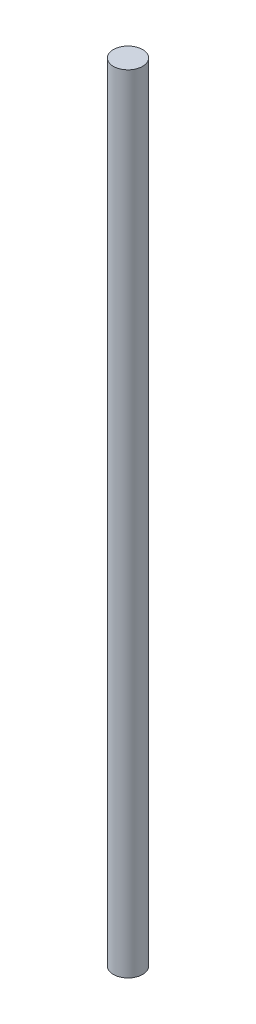
SolidWorks part; units mm, degrees
material "Custom Plastic"
ref_plane "Front Plane" through (0, 0, 0) normal (0, 0, 1) x (1, 0, 0)
ref_plane "Top Plane" through (0, 0, 0) normal (0, 1, 0) x (1, 0, 0)
ref_plane "Right Plane" through (0, 0, 0) normal (1, 0, 0) x (0, 0, -1)
sketch "Sketch1" plane through (0, 0, 0) normal (0, 1, 0) x (1, 0, 0)
  circle A0 centre (0, 0) radius 7.5
  dimension "D1" = 15
extrude "Boss-Extrude2" add sketch "Sketch1" along normal blind 404
